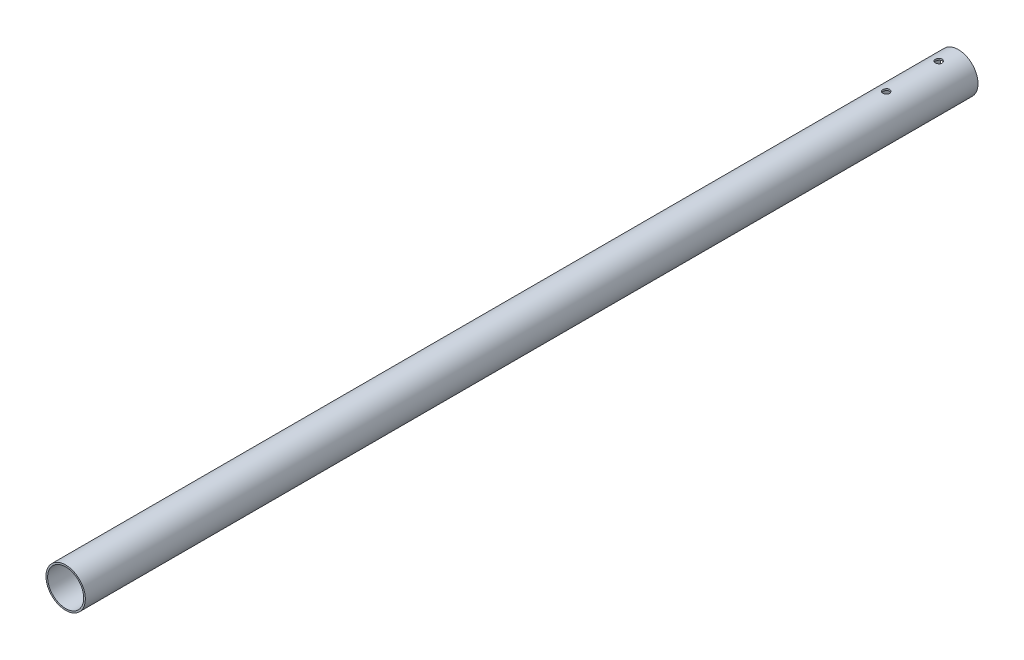
SolidWorks part; units mm, degrees
ref_plane "Alzado" through (0, 0, 0) normal (0, 0, 1) x (1, 0, 0)
ref_plane "Planta" through (0, 0, 0) normal (0, 1, 0) x (1, 0, 0)
ref_plane "Vista lateral" through (0, 0, 0) normal (1, 0, 0) x (0, 0, -1)
sketch "Croquis1" plane through (0, 0, 0) normal (0, 0, 1) x (1, 0, 0)
  circle A0 centre (0, 0) radius 19.05
  circle A1 centre (0, 0) radius 17.4625
  dimension "D1" = 38.1
  dimension "D2" = 1.5875
extrude "Saliente-Extruir1" add sketch "Croquis1" along normal blind 863.6
sketch "Croquis2" plane through (0, 0, 0) normal (0, 1, 0) x (1, 0, 0)
  line L0 (17.4625, 0) -> (-17.4625, 0) construction
  line L1 (19.05, 0) -> (-19.05, 0) construction
  circle A0 centre (0, -19.05) radius 3.2639
  circle A1 centre (0, -69.85) radius 3.2639
  dimension "D1" = 6.5278
  dimension "D2" = 19.05
  dimension "D3" = 69.85
extrude "Cortar-Extruir1" cut sketch "Croquis2" against normal through all and the other way through all
